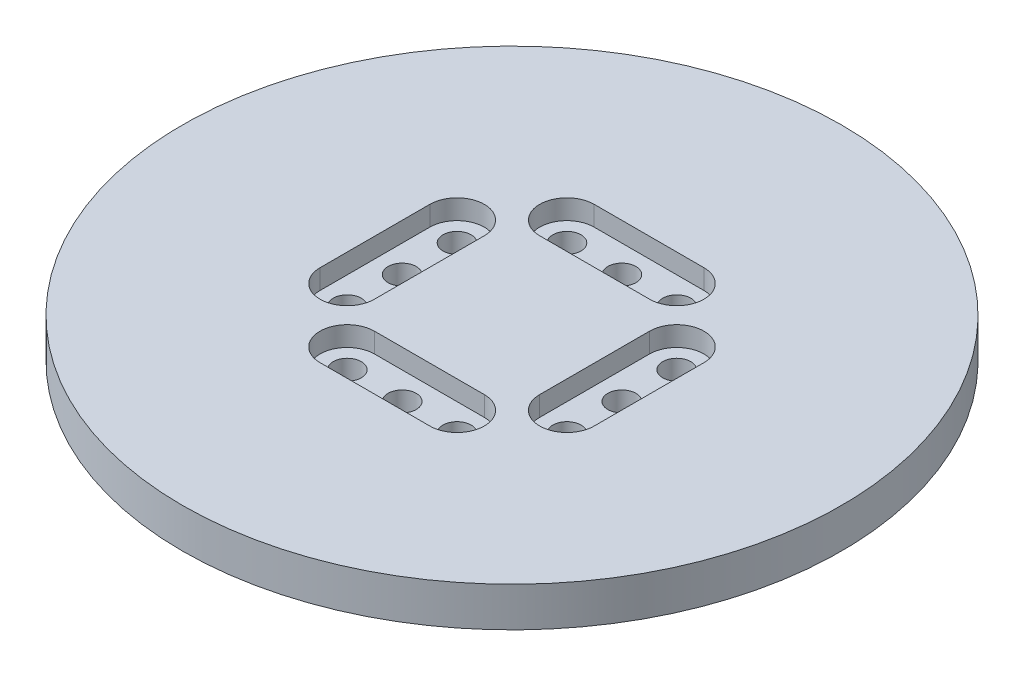
SolidWorks part; units mm, degrees
ref_plane "前视基准面" through (0, 0, 0) normal (0, 0, 1) x (1, 0, 0)
ref_plane "上视基准面" through (0, 0, 0) normal (0, 1, 0) x (1, 0, 0)
ref_plane "右视基准面" through (0, 0, 0) normal (1, 0, 0) x (0, 0, -1)
sketch "草图1" plane through (0, 0, 0) normal (0, 1, 0) x (1, 0, 0)
  circle A0 centre (0, 0) radius 45
extrude "凸台-拉伸1" add sketch "草图1" along normal blind 4
sketch "草图2" plane through (0, 4, 0) normal (0, 1, 0) x (1, 0, 0)
  circle A0 centre (0, 0) radius 75
  dimension "D1" = 150
extrude "凸台-拉伸2" add sketch "草图2" along normal blind 9
sketch "草图3" plane through (0, 13, 0) normal (0, 1, 0) x (1, 0, 0)
  circle A0 centre (-12.5, 25) radius 3.2
  circle A1 centre (0, 25) radius 3.2
  circle A2 centre (12.5, 25) radius 3.2
  circle A3 centre (25, 0) radius 3.2
  circle A4 centre (25, 12.5) radius 3.2
  circle A5 centre (25, -12.5) radius 3.2
  point P0 (0, 0)
  point P1 (0, 25)
  point P3 (25, 0)
  point P6 (-12.5, 25)
  point P7 (12.5, 25)
  dimension "D5" = 6.4
  dimension "D6" = 12.5
  dimension "D1" = 12.5
  dimension "D2" = 25
  dimension "D3" = 0
  dimension "D4" = 12.5
  dimension "D7" = 12.5
extrude "切除-拉伸1" cut sketch "草图3" against normal through all
mirror "镜向1" about plane through (0, 0, 0) normal (1, 0, 0) of "切除-拉伸1" second plane through (0, 0, 0) second plane normal (0, 0, 1)
sketch "草图4" plane through (0, 13, 0) normal (0, 1, 0) x (1, 0, 0)
  line L0 (-12.5, 31.2) -> (12.5, 31.2)
  line L2 (12.5, 18.8) -> (-12.5, 18.8)
  line L7 (-25, 12.5) -> (-25, -12.5) construction
  line L8 (-18.8, 12.5) -> (-18.8, -12.5)
  line L9 (-31.2, 12.5) -> (-31.2, -12.5)
  arc A0 (-12.5, 31.2) -> (-12.5, 18.8) centre (-12.5, 25) ccw
  arc A3 (12.5, 18.8) -> (12.5, 31.2) centre (12.5, 25) ccw
  arc A6 (-18.8, 12.5) -> (-31.2, 12.5) centre (-25, 12.5) ccw
  arc A7 (-31.2, -12.5) -> (-18.8, -12.5) centre (-25, -12.5) ccw
  point P3 (-25, 0)
  dimension "D1" = 6.2
  dimension "D2" = 6.2
extrude "切除-拉伸2" cut sketch "草图4" against normal blind 4.5
mirror "镜向2" about plane through (0, 0, 0) normal (1, 0, 0) of "切除-拉伸2" second plane through (0, 0, 0) second plane normal (0, 0, 1)
